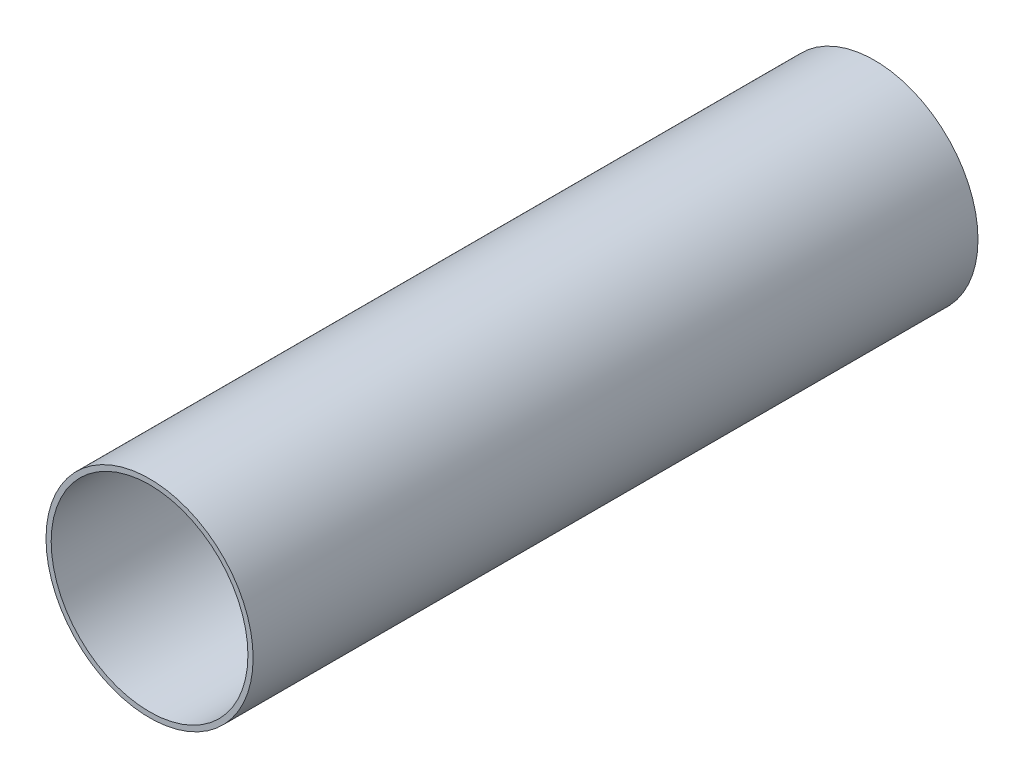
SolidWorks part; units mm, degrees
material "AISI 316 Stainless Steel Sheet (SS)"
ref_plane "Front Plane" through (0, 0, 0) normal (0, 0, 1) x (1, 0, 0)
ref_plane "Top Plane" through (0, 0, 0) normal (0, 1, 0) x (1, 0, 0)
ref_plane "Right Plane" through (0, 0, 0) normal (1, 0, 0) x (0, 0, -1)
sketch "Sketch1" plane through (0, 0, 0) normal (0, 0, 1) x (1, 0, 0)
  circle A0 centre (0, 0) radius 10
  circle A1 centre (0, 0) radius 9.5
  dimension "D1" = 20
  dimension "D2" = 19
extrude "Boss-Extrude1" add sketch "Sketch1" along normal blind 70
sketch "Sketch2" plane through (0, 0, 0) normal (0, 0, 1) x (1, 0, 0)
  circle A0 centre (0, 0) radius 10
  dimension "D1" = 20
sketch "Sketch3" plane through (0, 0, 70) normal (0, 0, 1) x (1, 0, 0)
  circle A0 centre (0, 0) radius 10
  dimension "D1" = 20
equation "\"1cmcm\"=0.002"
